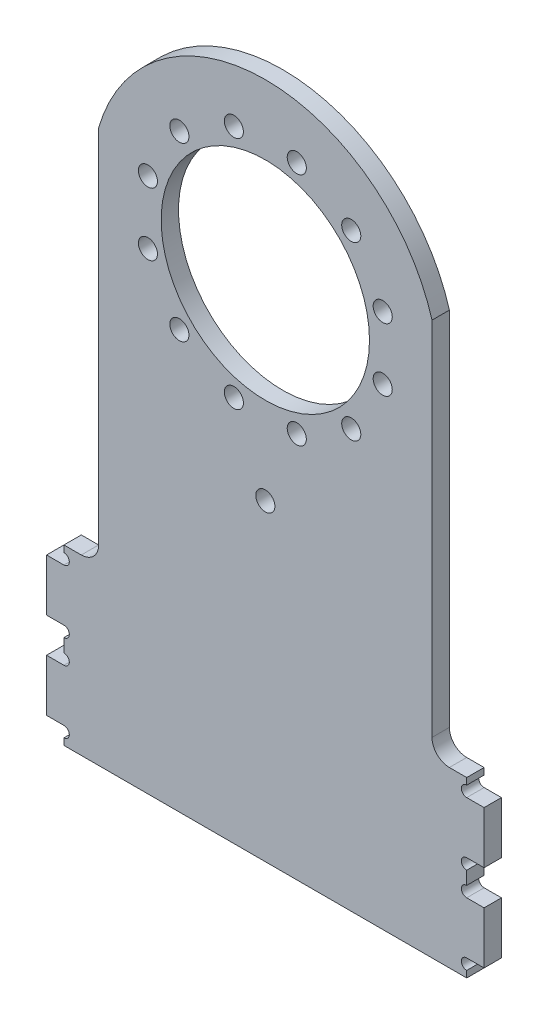
SolidWorks part; units mm, degrees
material "6061 合金"
ref_plane "前视基准面" through (0, 0, 0) normal (0, 0, 1) x (1, 0, 0)
ref_plane "上视基准面" through (0, 0, 0) normal (0, 1, 0) x (1, 0, 0)
ref_plane "右视基准面" through (0, 0, 0) normal (1, 0, 0) x (0, 0, -1)
other "Configuration Table"
sketch "草图1" plane through (0, 0, 0) normal (0, 0, 1) x (1, 0, 0)
  line L0 (0, 0) -> (0, 150.9585) construction
  line L3 (-48, 109.07) -> (-48, 0)
  line L4 (-48, 0) -> (48, 0)
  line L5 (48, 109.07) -> (48, 0)
  circle A0 centre (0, 95.07) radius 30
  arc A2 (48, 109.07) -> (-48, 109.07) centre (0, 95.07) ccw
  dimension "D3" = 60
  dimension "D4" = 50
  dimension "D1" = 96
  dimension "D2" = 95.07
extrude "凸台-拉伸1" add sketch "草图1" along normal blind 5
sketch "草图2" plane through (0, 0, 0) normal (0, -1, 0) x (1, 0, 0)
  line L0 (-53.8408, 2.5) -> (58.1589, 2.5) construction
  line L1 (0, 20.308) -> (0, -17.9139) construction
  line L2 (-48, 5) -> (48, 5) construction
  line L3 (-48, 0) -> (48, 0) construction
  circle A0 centre (35, 2.5) radius 2.75
  circle A1 centre (-35, 2.5) radius 2.75
  dimension "D2" = 5.5
  dimension "D1" = 70
extrude "切除-拉伸1" [suppressed] cut sketch "草图2" against normal blind 50
sketch "草图3" plane through (0, 0, 5) normal (0, 0, 1) x (1, 0, 0)
  line L0 (0, 0) -> (0, 95.092) construction
  circle A0 centre (0, 40) radius 2.75
  dimension "D1" = 5.5
  dimension "D2" = 40
extrude "切除-拉伸2" cut sketch "草图3" against normal blind 20
sketch "草图4" plane through (0, 0, 5) normal (0, 0, 1) x (1, 0, 0)
  line L0 (0, 95.07) -> (0, 148.0466) construction
  line L1 (0, 95.07) -> (15.7821, 153.9695) construction
  circle A0 centre (9.0587, 128.8774) radius 2.75
  circle A1 centre (24.7487, 119.8187) radius 2.75
  circle A2 centre (33.8074, 104.1287) radius 2.75
  circle A3 centre (33.8074, 86.0113) radius 2.75
  circle A4 centre (24.7487, 70.3213) radius 2.75
  circle A5 centre (9.0587, 61.2626) radius 2.75
  circle A6 centre (-9.0587, 61.2626) radius 2.75
  circle A7 centre (-24.7487, 70.3213) radius 2.75
  circle A8 centre (-33.8074, 86.0113) radius 2.75
  circle A9 centre (-33.8074, 104.1287) radius 2.75
  circle A10 centre (-24.7487, 119.8187) radius 2.75
  circle A11 centre (-9.0587, 128.8774) radius 2.75
  point P8 (0, 95.07)
  point P31 (0, 95.07)
  dimension "D1" = 5.5
  dimension "D2" = 35
  dimension "D3" = 15
  dimension "D4" = 12
extrude "切除-拉伸3" cut sketch "草图4" against normal blind 10
sketch "草图5" plane through (0, 0, 5) normal (0, 0, 1) x (1, 0, 0)
  line L0 (0, 0) -> (0, 169.4961) construction
  line L2 (-58, 0) -> (58, 0)
  line L3 (-58, 0) -> (-58, -50)
  line L4 (-58, -50) -> (58, -50)
  line L5 (58, 0) -> (58, -50)
  dimension "D1" = 116
  dimension "D2" = 50
extrude "凸台-拉伸2" add sketch "草图5" against normal up to surface (5 mm away) up to face at (27.4987, 119.8187, 0)
sketch "草图6" plane through (0, 0, 5) normal (0, 0, 1) x (1, 0, 0)
  line L0 (0, 0) -> (0, -61.5724) construction
  line L2 (45, -5) -> (50.2, -5)
  line L3 (45, -5) -> (45, -20.2)
  line L4 (45, -20.2) -> (50.2, -20.2)
  line L5 (50.2, -5) -> (50.2, -20.2)
  line L6 (45, -30.2) -> (50.2, -30.2)
  line L7 (45, -30.2) -> (45, -45.4)
  line L8 (45, -45.4) -> (50.2, -45.4)
  line L9 (50.2, -30.2) -> (50.2, -45.4)
  line L10 (-50.2, -30.2) -> (-50.2, -45.4)
  line L11 (-45, -45.4) -> (-50.2, -45.4)
  line L12 (-45, -30.2) -> (-45, -45.4)
  line L13 (-45, -30.2) -> (-50.2, -30.2)
  line L14 (-50.2, -5) -> (-50.2, -20.2)
  line L15 (-45, -20.2) -> (-50.2, -20.2)
  line L16 (-45, -5) -> (-45, -20.2)
  line L17 (-45, -5) -> (-50.2, -5)
  line L18 (58, 0) -> (48, 0) construction
  dimension "D1" = 5.2
  dimension "D2" = 15.2
  dimension "D3" = 15.2
  dimension "D4" = 45
  dimension "D5" = 10
  dimension "D6" = 5
extrude "切除-拉伸4" [suppressed] cut sketch "草图6" against normal through all both
sketch "草图7" [suppressed] plane through (0, 0, 5) normal (0, 0, 1) x (1, 0, 0)
  line L0 (50.2, -20.2) -> (50.2, -5) construction
  line L1 (45, -5) -> (45, -20.2) construction
  line L2 (50.2, -45.4) -> (50.2, -30.2) construction
  line L3 (45, -30.2) -> (45, -45.4) construction
  line L4 (50.2, -5) -> (45, -5) construction
  line L5 (45, -20.2) -> (50.2, -20.2) construction
  line L6 (50.2, -30.2) -> (45, -30.2) construction
  line L7 (45, -45.4) -> (50.2, -45.4) construction
  line L8 (0, 0) -> (0, -72.6402) construction
  circle A0 centre (50.2, -6.55) radius 1.55
  circle A1 centre (50.2, -18.65) radius 1.55
  circle A2 centre (45, -6.55) radius 1.55
  circle A3 centre (45, -18.65) radius 1.55
  circle A4 centre (50.2, -31.75) radius 1.55
  circle A5 centre (45, -31.75) radius 1.55
  circle A6 centre (50.2, -43.85) radius 1.55
  circle A7 centre (45, -43.85) radius 1.55
  circle A8 centre (-45, -43.85) radius 1.55
  circle A9 centre (-50.2, -43.85) radius 1.55
  circle A10 centre (-45, -31.75) radius 1.55
  circle A11 centre (-50.2, -31.75) radius 1.55
  circle A12 centre (-45, -18.65) radius 1.55
  circle A13 centre (-45, -6.55) radius 1.55
  circle A14 centre (-50.2, -18.65) radius 1.55
  circle A15 centre (-50.2, -6.55) radius 1.55
  dimension "D1" = 3.1
extrude "切除-拉伸5" [suppressed] cut sketch "草图7" against normal through all both
sketch "草图8" plane through (0, 0, 5) normal (0, 0, 1) x (1, 0, 0)
  line L0 (0, 22.7135) -> (0, -60.4554) construction
  line L1 (58, -50) -> (58, 0) construction
  line L2 (58, -5) -> (63, -5)
  line L3 (58, -5) -> (58, -20)
  line L4 (58, -20) -> (63, -20)
  line L5 (63, -5) -> (63, -20)
  line L6 (58, 0) -> (48, 0) construction
  line L7 (58, -30) -> (63, -30)
  line L8 (58, -30) -> (58, -45)
  line L9 (58, -45) -> (63, -45)
  line L10 (63, -30) -> (63, -45)
  line L11 (-63, -30) -> (-63, -45)
  line L12 (-58, -45) -> (-63, -45)
  line L13 (-58, -30) -> (-58, -45)
  line L14 (-58, -30) -> (-63, -30)
  line L15 (-63, -5) -> (-63, -20)
  line L16 (-58, -20) -> (-63, -20)
  line L17 (-58, -5) -> (-58, -20)
  line L18 (-58, -5) -> (-63, -5)
  dimension "D1" = 5
  dimension "D2" = 15
  dimension "D3" = 5
  dimension "D4" = 10
  dimension "D5" = 15
extrude "凸台-拉伸3" add sketch "草图8" against normal up to surface (5 mm away) up to face at (27.4987, 119.8187, 0)
sketch "草图9" plane through (0, 0, 5) normal (0, 0, 1) x (1, 0, 0)
  line L0 (58, -5) -> (58, 0) construction
  line L1 (58, -30) -> (58, -20) construction
  line L2 (58, -50) -> (58, -45) construction
  line L3 (63, -5) -> (58, -5) construction
  line L4 (58, -20) -> (63, -20) construction
  line L5 (63, -30) -> (58, -30) construction
  line L6 (58, -45) -> (63, -45) construction
  line L7 (0, 0) -> (0, -84.76) construction
  circle A0 centre (58, -3.45) radius 1.55
  circle A1 centre (58, -21.55) radius 1.55
  circle A2 centre (58, -28.45) radius 1.55
  circle A3 centre (58, -46.55) radius 1.55
  circle A4 centre (-58, -46.55) radius 1.55
  circle A5 centre (-58, -28.45) radius 1.55
  circle A6 centre (-58, -21.55) radius 1.55
  circle A7 centre (-58, -3.45) radius 1.55
  dimension "D1" = 3.1
extrude "切除-拉伸6" cut sketch "草图9" against normal up to surface (5 mm away) up to face at (27.4987, 119.8187, 0)
fillet "圆角1" radius 5 2 edges at (-48, 0, 2.5) (48, 0, 2.5)
